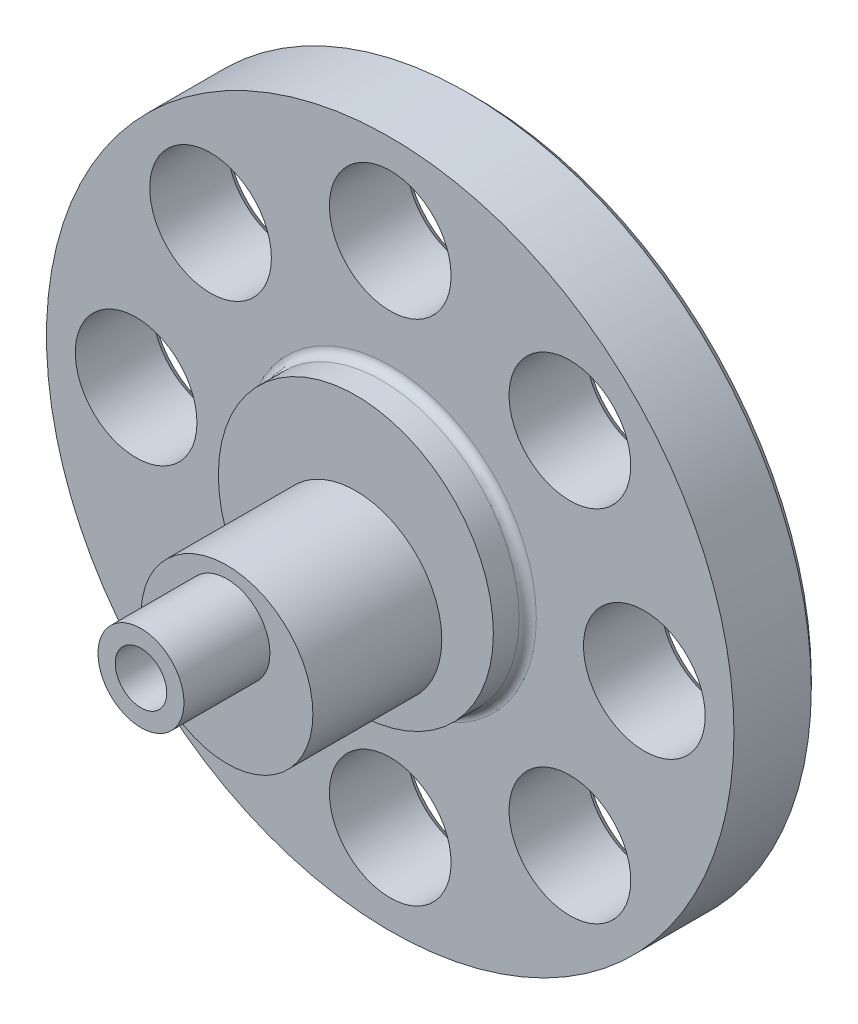
SolidWorks part; units mm, degrees
material "ABS PC"
ref_plane "Front Plane" through (0, 0, 0) normal (0, 0, 1) x (1, 0, 0)
ref_plane "Top Plane" through (0, 0, 0) normal (0, 1, 0) x (1, 0, 0)
ref_plane "Right Plane" through (0, 0, 0) normal (1, 0, 0) x (0, 0, -1)
sketch "Sketch1" plane through (0, 0, 0) normal (0, 0, 1) x (1, 0, 0)
  circle A2 centre (0, 0) radius 20
  circle A10 centre (-14.784, 0) radius 3.54
  circle A11 centre (-10.4538, -10.4538) radius 3.54
  circle A12 centre (0, -14.784) radius 3.54
  circle A13 centre (10.4538, -10.4538) radius 3.54
  circle A14 centre (14.784, 0) radius 3.54
  circle A15 centre (10.4538, 10.4538) radius 3.54
  circle A16 centre (0, 14.784) radius 3.54
  circle A17 centre (-10.4538, 10.4538) radius 3.54
  dimension "D1" = 7.08
  dimension "D2" = 40
extrude "Boss-Extrude1" add sketch "Sketch1" along normal blind 5
sketch "Sketch2" plane through (0, 0, 5) normal (0, 0, 1) x (1, 0, 0)
  circle A0 centre (0, 0) radius 8
  dimension "D1" = 16
extrude "Boss-Extrude2" add sketch "Sketch2" along normal blind 2
sketch "Sketch3" plane through (0, 0, 0) normal (0, 0, -1) x (-1, 0, 0)
  circle A0 centre (0, 0) radius 6.5
  dimension "D1" = 13
extrude "Cut-Extrude1" cut sketch "Sketch3" against normal blind 6
sketch "Sketch4" plane through (0, 0, 7) normal (0, 0, 1) x (1, 0, 0)
  circle A0 centre (0, -1.812) radius 5
  dimension "D2" = 10
  dimension "D1" = 1.812
extrude "Boss-Extrude3" add sketch "Sketch4" along normal blind 7.5
sketch "Sketch5" plane through (0, 0, 14.5) normal (0, 0, 1) x (1, 0, 0)
  circle A0 centre (0, 0) radius 2.5
  dimension "D1" = 5
extrude "Boss-Extrude4" add sketch "Sketch5" along normal blind 5
fillet "Fillet1" radius 0.5 1 edges at (8, 0, 5)
sketch "Sketch6" plane through (0, 0, 0) normal (0, 0, -1) x (-1, 0, 0)
  circle A0 centre (0, 0) radius 6.5
  circle A1 centre (0, 0) radius 3.5
  dimension "D1" = 7
extrude "Boss-Extrude5" [suppressed] add sketch "Sketch6" against normal blind 6
chamfer "Chamfer1" distance 0.5 angle 45 10 edges at (-6.9138, 10.4538, 0) (3.54, 14.784, 0) (13.9938, 10.4538, 0) (18.324, 0, 0) (13.9938, -10.4538, 0) (3.54, -14.784, 0) (-6.9138, -10.4538, 0) (-11.244, 0, 0) (20, 0, 0) (-6.5, 0, 0)
sketch "Sketch7" plane through (0, 0, 19.5) normal (0, 0, 1) x (1, 0, 0)
  circle A0 centre (0, 0) radius 1.5
  dimension "D1" = 3
extrude "Cut-Extrude2" cut sketch "Sketch7" against normal blind 15
